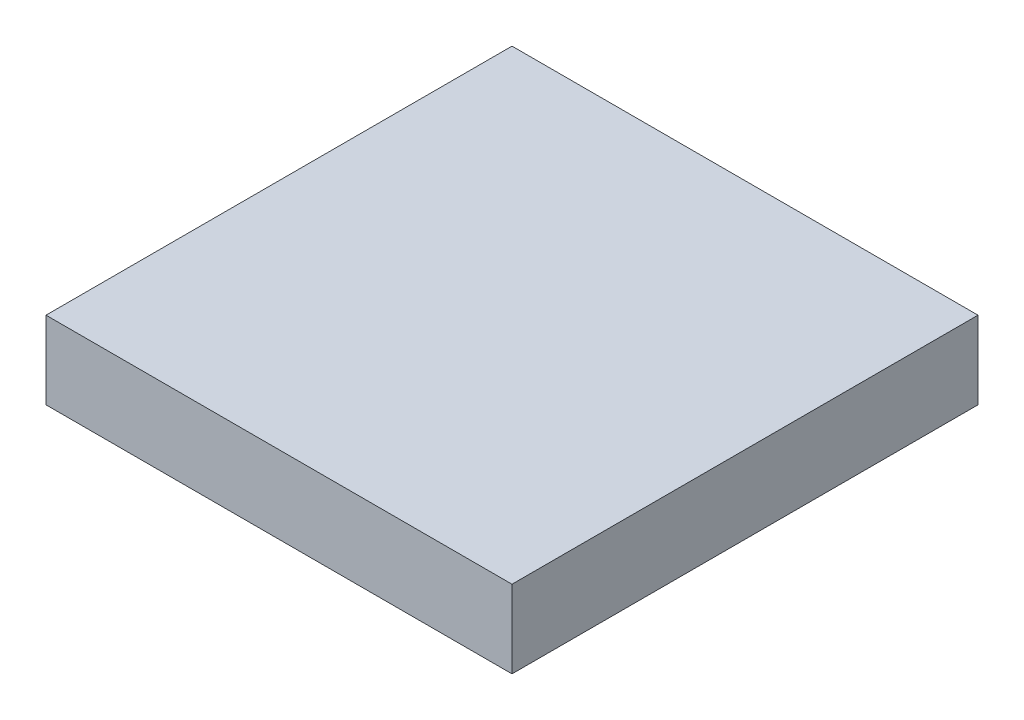
SolidWorks part; units mm, degrees
ref_plane "Front Plane" through (0, 0, 0) normal (0, 0, 1) x (1, 0, 0)
ref_plane "Top Plane" through (0, 0, 0) normal (0, 1, 0) x (1, 0, 0)
ref_plane "Right Plane" through (0, 0, 0) normal (1, 0, 0) x (0, 0, -1)
sketch "Sketch1" plane through (0, 0, 0) normal (0, 1, 0) x (1, 0, 0)
  line L1 (300, -300) -> (-300, -300)
  line L2 (300, -300) -> (300, 300)
  line L3 (300, 300) -> (-300, 300)
  line L4 (-300, -300) -> (-300, 300)
  line L5 (300, -300) -> (-300, 300) construction
  line L6 (300, 300) -> (-300, -300) construction
  point P0 (0, 0)
  dimension "D1" = 600
  dimension "D2" = 600
extrude "Boss-Extrude1" add sketch "Sketch1" along normal blind 100
